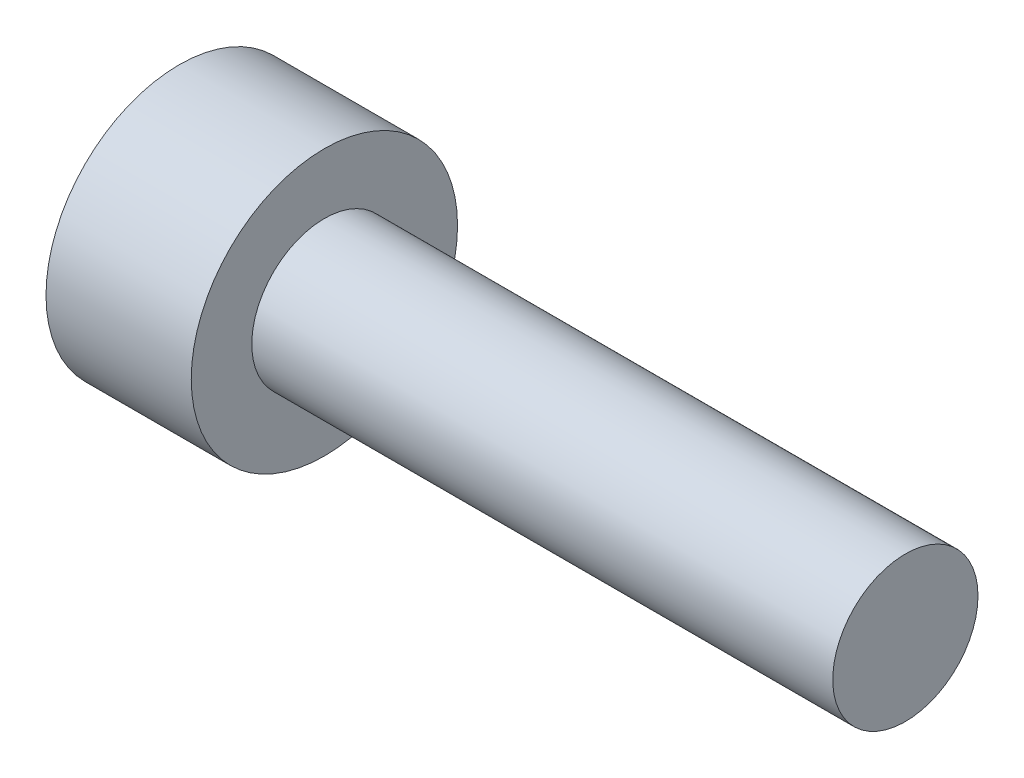
SolidWorks part; units mm, degrees
other "Preload Thrust Plate M3 Bolt"
ref_plane "Front Plane" through (0, 0, 0) normal (0, 0, 1) x (1, 0, 0)
ref_plane "Top Plane" through (0, 0, 0) normal (0, 1, 0) x (1, 0, 0)
ref_plane "Right Plane" through (0, 0, 0) normal (1, 0, 0) x (0, 0, -1)
sketch3d "M3 shank sketch datum points"
  point P0 (13, -38, -11.5)
  point P1 (13, -28, -11.5)
  point P2 (13, -38, -1.5)
ref_plane "M3 shank sketch plane" through (13, 0, 0) normal (1, 0, 0) x (0, 0, -1)
sketch "M3 shank sketch" plane through (13, 0, 0) normal (1, 0, 0) x (0, 0, -1)
  circle A0 centre (11.5, -38) radius 1.5
extrude "M3 shank" add sketch "M3 shank sketch" along normal blind 12 separate body
sketch3d "M3 screw head sketch datum points"
  point P0 (10, -38, -11.5)
  point P1 (10, -28, -11.5)
  point P2 (10, -38, -1.5)
ref_plane "M3 screw head sketch plane" through (10, 0, 0) normal (1, 0, 0) x (0, 0, -1)
sketch "M3 screw head sketch" plane through (10, 0, 0) normal (1, 0, 0) x (0, 0, -1)
  circle A0 centre (11.5, -38) radius 2.75
extrude "M3 screw head" add sketch "M3 screw head sketch" along normal blind 3
